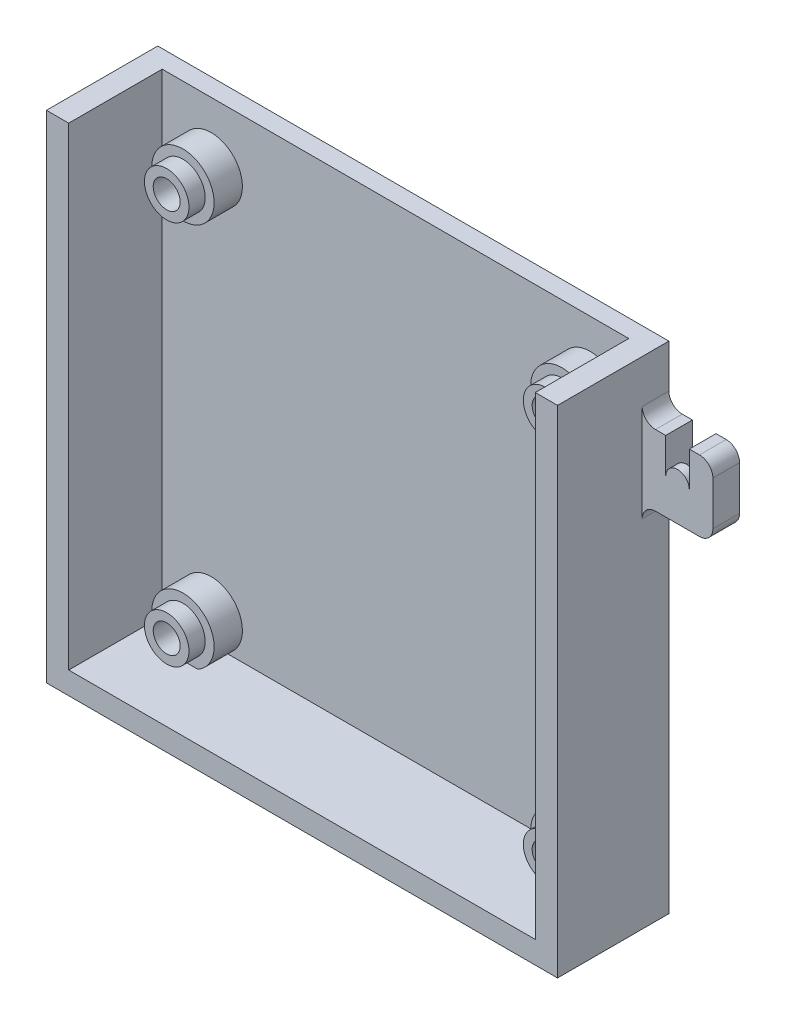
SolidWorks part; units mm, degrees
material "ABS"
ref_plane "X-Y Datum" through (0, 0, 0) normal (0, 0, 1) x (1, 0, 0)
ref_plane "X-Z Datum" through (0, 0, 0) normal (0, 1, 0) x (1, 0, 0)
ref_plane "Y-Z Datum" through (0, 0, 0) normal (1, 0, 0) x (0, 0, -1)
sketch "Sketch1" plane through (0, 0, 0) normal (0, 0, 1) x (1, 0, 0)
  line L1 (-52.3875, 53.1812) -> (52.3875, 53.1812)
  line L2 (-52.3875, 53.1812) -> (-52.3875, -53.1812)
  line L3 (-52.3875, -53.1812) -> (52.3875, -53.1812)
  line L4 (52.3875, 53.1812) -> (52.3875, -53.1812)
  line L5 (-52.3875, 53.1812) -> (52.3875, -53.1812) construction
  line L6 (-52.3875, -53.1812) -> (52.3875, 53.1812) construction
  point P0 (0, 0)
  dimension "D1" = 104.775
  dimension "D2" = 106.3625
extrude "Boss-Extrude1" add sketch "Sketch1" along normal blind 4
sketch "Sketch2" plane through (0, 0, 0) normal (0, 0, 1) x (1, 0, 0)
  line L1 (-57.3875, -53.1812) -> (-57.3875, -58.1813)
  line L2 (-57.3875, 53.1812) -> (-57.3875, -53.1812)
  line L4 (57.3875, 53.1812) -> (52.3875, 53.1812)
  line L5 (57.3875, -58.1812) -> (57.3875, 53.1812)
  line L6 (-52.3875, -58.1812) -> (57.3875, -58.1812)
  line L7 (57.3875, -58.1812) -> (57.3875, 53.1812)
  line L8 (-52.3875, -58.1812) -> (57.3875, -58.1812)
  line L9 (52.3875, -53.1812) -> (52.3875, 53.1812) construction
  line L10 (-52.3875, -53.1812) -> (52.3875, -53.1812) construction
  line L11 (52.3875, -53.1812) -> (52.3875, 53.1812)
  line L12 (-52.3875, -53.1812) -> (52.3875, -53.1812)
  line L13 (-57.3875, 53.1812) -> (-57.3875, -53.1812)
  line L14 (-57.3875, -58.1813) -> (-52.3875, -58.1812)
  line L15 (-57.3875, 53.1812) -> (-52.3875, 53.1812)
  line L16 (-52.3875, 53.1812) -> (-52.3875, -53.1812) construction
  line L17 (-52.3875, 53.1812) -> (-52.3875, -53.1812)
  dimension "D1" = 5
  dimension "D2" = 5
extrude "Boss-Extrude2" add sketch "Sketch2" along normal blind 25
sketch "Sketch3" plane through (0, 0, 4) normal (0, 0, 1) x (1, 0, 0)
  circle A0 centre (-41.382, 39.351) radius 3.025
  circle A1 centre (43.708, 39.351) radius 3.025
  circle A2 centre (43.708, -47.009) radius 3.025
  circle A3 centre (-41.382, -47.009) radius 3.025
  circle A4 centre (43.708, 39.351) radius 5
  circle A5 centre (-41.382, 39.351) radius 5
  circle A6 centre (-41.382, -47.009) radius 5
  circle A7 centre (43.708, -47.009) radius 5
  point P0 (-41.382, 39.351)
  point P1 (-41.382, -47.009)
  point P3 (43.708, -47.009)
  point P5 (43.708, 39.351)
  dimension "D1" = 6.05
  dimension "D2" = 10
extrude "Boss-Extrude3" add sketch "Sketch3" along normal blind 10
sketch "Sketch4" plane through (0, 0, 4) normal (0, 0, 1) x (1, 0, 0)
  circle A0 centre (43.708, 39.351) radius 7
  circle A1 centre (-41.382, 39.351) radius 7
  circle A2 centre (-41.382, -47.009) radius 7
  circle A3 centre (43.708, -47.009) radius 7
  circle A5 centre (-41.382, -47.009) radius 3.025
  circle A6 centre (-41.382, -47.009) radius 3.025
  circle A7 centre (43.708, -47.009) radius 3.025
  circle A8 centre (43.708, -47.009) radius 3.025
  circle A9 centre (43.708, 39.351) radius 3.025
  circle A10 centre (43.708, 39.351) radius 3.025
  circle A11 centre (-41.382, 39.351) radius 3.025
  circle A12 centre (-41.382, 39.351) radius 3.025
  dimension "D1" = 14
  dimension "D2" = 0
  dimension "D3" = 0
  dimension "D4" = 0
  dimension "D5" = 0
extrude "Boss-Extrude4" add sketch "Sketch4" along normal blind 6.35
sketch "Sketch6" plane through (0, 0, 0) normal (0, 0, 1) x (1, 0, 0)
  line L0 (-73.2675, -42.3012) -> (-57.3875, -58.1813) construction
  line L5 (57.3875, -58.1812) -> (57.3875, 53.1812) construction
  line L6 (57.3875, 40.4812) -> (73.2625, 40.4812)
  line L7 (57.3875, 40.4812) -> (57.3875, 24.6062)
  line L8 (57.3875, 24.6062) -> (73.2625, 24.6062)
  line L9 (73.2625, 40.4812) -> (73.2625, 24.6062)
  line L10 (57.3875, 24.6062) -> (73.2625, 40.4812)
  line L11 (57.3875, 53.1812) -> (52.3875, 53.1812) construction
  line L13 (-57.3875, -58.1813) -> (-73.2675, -58.1813)
  line L14 (-57.3875, -58.1813) -> (-57.3875, -42.3012)
  line L15 (-57.3875, -42.3012) -> (-73.2675, -42.3012)
  line L17 (-73.2675, -58.1813) -> (-73.2675, -42.3012)
  circle A1 centre (65.325, 32.5438) radius 2 construction
  circle A2 centre (-65.3275, -50.2413) radius 2 construction
  dimension "D1" = 15.88
  dimension "D6" = 4
  dimension "D2" = 4
  dimension "D4" = 15.875
  dimension "D5" = 15.875
  dimension "D7" = 12.7
extrude "Boss-Extrude5" add sketch "Sketch6" along normal blind 6
hole_wizard "M5 Clearance Hole2" positions "Sketch7" profile "Sketch8" hole size "M5" standard "ANSI Metric"
sketch "Sketch7" plane through (0, 0, 4) normal (0, 0, 1) x (1, 0, 0)
  point P0 (65.325, 32.5438)
  point P8 (-65.3275, -50.2413)
sketch "Sketch8" plane through (65.325, 32.5438, 4) normal (1, 0, 0) x (0, -1, 0)
  line L0 (0, 0) -> (0, 4)
  line L1 (0, 4) -> (2.65, 4)
  line L2 (2.65, 4) -> (2.65, 0)
  line L5 (2.65, 0) -> (0, 0)
  line L11 (0, -6.35) -> (0, 107.95) construction
  dimension "Thru Hole Dia." = 5.3
  dimension "Thru Hole Depth" = 4
fillet "Fillet2" radius 3 6 edges at (73.2625, 24.6062, 3) (73.2625, 40.4812, 3) (57.3875, 40.4812, 3) (57.3875, 24.6062, 3) (-73.2675, -58.1813, 3) (-73.2675, -42.3012, 3)
sketch "Sketch9" plane through (0, 0, 25) normal (0, 0, 1) x (1, 0, 0)
  line L0 (-52.3875, 38.1812) -> (-57.3875, 38.1812)
  line L1 (-52.3875, -53.1812) -> (-57.3875, -53.1812)
  line L8 (-52.3875, -53.1812) -> (-52.3875, 53.1812)
  line L9 (-52.3875, 53.1812) -> (-57.3875, 53.1812)
  line L10 (-57.3875, 53.1812) -> (-57.3875, -58.1813)
  line L11 (-57.3875, -58.1813) -> (57.3875, -58.1812)
  line L12 (57.3875, -58.1812) -> (57.3875, 53.1812)
  line L13 (57.3875, 53.1812) -> (52.3875, 53.1812)
  line L14 (52.3875, 53.1812) -> (52.3875, -53.1812)
  line L15 (52.3875, -53.1812) -> (-52.3875, -53.1812)
  line L16 (-52.3875, -53.1812) -> (-52.3875, 53.1812)
  line L17 (-52.3875, 53.1812) -> (-57.3875, 53.1812)
  line L18 (-57.3875, 53.1812) -> (-57.3875, -58.1813)
  line L19 (-57.3875, -58.1813) -> (57.3875, -58.1812)
  line L20 (57.3875, -58.1812) -> (57.3875, 53.1812)
  line L21 (57.3875, 53.1812) -> (52.3875, 53.1812)
  line L22 (52.3875, 53.1812) -> (52.3875, -53.1812)
  line L23 (52.3875, -53.1812) -> (-52.3875, -53.1812)
  line M12 (-57.3875, 53.1812) -> (-57.3875, -58.1813)
  line M13 (-57.3875, -58.1813) -> (57.3875, -58.1812)
  line M14 (57.3875, -58.1812) -> (57.3875, 53.1812)
  line M15 (57.3875, 53.1812) -> (52.3875, 53.1812)
  line M16 (52.3875, 53.1812) -> (52.3875, -53.1812)
  line M17 (52.3875, -53.1812) -> (-52.3875, -53.1812)
  dimension "D2" = 15
  dimension "D1" = 0
extrude "Boss-Extrude6" [suppressed] add sketch "Sketch9" along normal blind 25 contours L1 M17 M12 M13 M14 M15 M16 | L16 L17 L18 L19 L20 L21 L22 L23
fillet "Fillet3" [suppressed] radius 1
ref_plane "Plane1" through (0, 0, 30) normal (0, 0, -1) x (-1, 0, 0)
sketch "Sketch10" [suppressed] plane through (0, 0, 30) normal (0, 0, -1) x (-1, 0, 0)
  line L0 (-56.3875, -57.1812) -> (56.3875, -57.1812) construction
  line L1 (56.3875, -57.1812) -> (56.3875, -58.1812) construction
  line L2 (56.3875, -58.1812) -> (-56.3875, -58.1812) construction
  line L3 (-57.3875, -57.1812) -> (-57.3875, 53.1812) construction
  line L4 (-57.3875, 53.1812) -> (-56.3875, 52.1812) construction
  line L5 (-56.3875, 52.1812) -> (-56.3875, -57.1812) construction
  line L6 (-56.3875, -58.1812) -> (56.3875, -58.1812) construction
  line L7 (-56.3875, -57.1812) -> (56.3875, -57.1812)
  line L8 (56.3875, -57.1812) -> (56.3875, -58.1812)
  line L9 (56.3875, -58.1812) -> (-56.3875, -58.1812)
  line L10 (-57.3875, -57.1812) -> (-57.3875, 53.1812)
  line L11 (-57.3875, 53.1812) -> (-56.3875, 52.1812)
  line L12 (-56.3875, 52.1812) -> (-56.3875, -57.1812)
  line L13 (-56.3875, -58.1812) -> (56.3875, -58.1812)
  line L14 (-53.3875, -54.1812) -> (-59.0444, -59.8381)
  line L15 (-53.5444, -65.3381) -> (-46.3875, -58.1813)
  line L16 (-53.5444, -54.3381) -> (-64.5444, -54.3381)
  line L17 (-53.5444, -54.3381) -> (-53.5444, -65.3381)
  line L18 (-53.5444, -65.3381) -> (-64.5444, -65.3381)
  line L19 (-64.5444, -54.3381) -> (-64.5444, -65.3381)
  line L20 (-53.5444, -54.3381) -> (-64.5444, -65.3381) construction
  line L21 (-53.5444, -65.3381) -> (-64.5444, -54.3381) construction
  line L26 (-62.0444, -58.3381) -> (-60.5444, -56.8381)
  line L27 (-56.0444, -58.3381) -> (-62.0444, -58.3381)
  line L28 (-64.5444, -54.3381) -> (-57.3875, -47.1813)
  line L29 (-56.0444, -58.3381) -> (-56.0444, -61.3381)
  line L30 (-56.0444, -61.3381) -> (-62.0444, -61.3381)
  line L31 (-62.0444, -58.3381) -> (-62.0444, -61.3381)
  line L32 (-56.0444, -58.3381) -> (-62.0444, -61.3381) construction
  line L33 (-56.0444, -61.3381) -> (-62.0444, -58.3381) construction
  line L34 (-57.5444, -56.8381) -> (-60.5444, -56.8381)
  line L35 (-57.5444, -56.8381) -> (-57.5444, -62.8381)
  line L36 (-57.5444, -62.8381) -> (-60.5444, -62.8381)
  line L37 (-60.5444, -56.8381) -> (-60.5444, -62.8381)
  line L38 (-57.5444, -56.8381) -> (-60.5444, -62.8381) construction
  line L39 (-57.5444, -62.8381) -> (-60.5444, -56.8381) construction
  line L40 (-57.5444, -62.8381) -> (-56.0444, -61.3381)
  line L41 (-56.0444, -61.3381) -> (-60.5444, -56.8381)
  line L42 (-57.5444, -62.8381) -> (-62.0444, -58.3381)
  arc A0 (-57.3875, -57.1812) -> (-56.3875, -58.1812) centre (-56.3875, -57.1812) ccw construction
  arc A1 (-57.3875, -57.1812) -> (-56.3875, -58.1812) centre (-56.3875, -57.1812) ccw
  dimension "D1" = 3
  dimension "D2" = 11
  dimension "D3" = 11
  dimension "D4" = 45
  dimension "D5" = 45
  dimension "D6" = 6
  dimension "D7" = 8
  dimension "D8" = 3
  dimension "D9" = 6
  dimension "D10" = 6.364
extrude "Boss-Extrude7" [suppressed] add sketch "Sketch10" along normal blind 6
fillet "Fillet4" [suppressed] radius 6
fillet "Fillet5" [suppressed] radius 1.5
sketch "Sketch11" plane through (0, 0, 6) normal (0, 0, 1) x (1, 0, 0)
  line L0 (-67.9775, -50.2413) -> (-67.9775, -42.3012)
  line L1 (-57.3875, -42.3012) -> (-70.2675, -42.3012) construction
  line L2 (-62.6775, -50.2413) -> (-62.6775, -42.3012)
  line L3 (62.675, 32.5438) -> (62.675, 40.4812)
  line L4 (60.3875, 40.4812) -> (70.2625, 40.4812) construction
  line L5 (67.975, 32.5438) -> (67.975, 40.4812)
  line L6 (60.3875, 40.4812) -> (70.2625, 40.4812)
  line L7 (-57.3875, -42.3012) -> (-70.2675, -42.3012)
  circle A0 centre (-65.3275, -50.2413) radius 2.65 construction
  circle A1 centre (65.325, 32.5438) radius 2.65 construction
  circle A2 centre (65.325, 32.5438) radius 2.65
  circle A3 centre (-65.3275, -50.2413) radius 2.65
extrude "Cut-Extrude1" cut sketch "Sketch11" against normal through all
